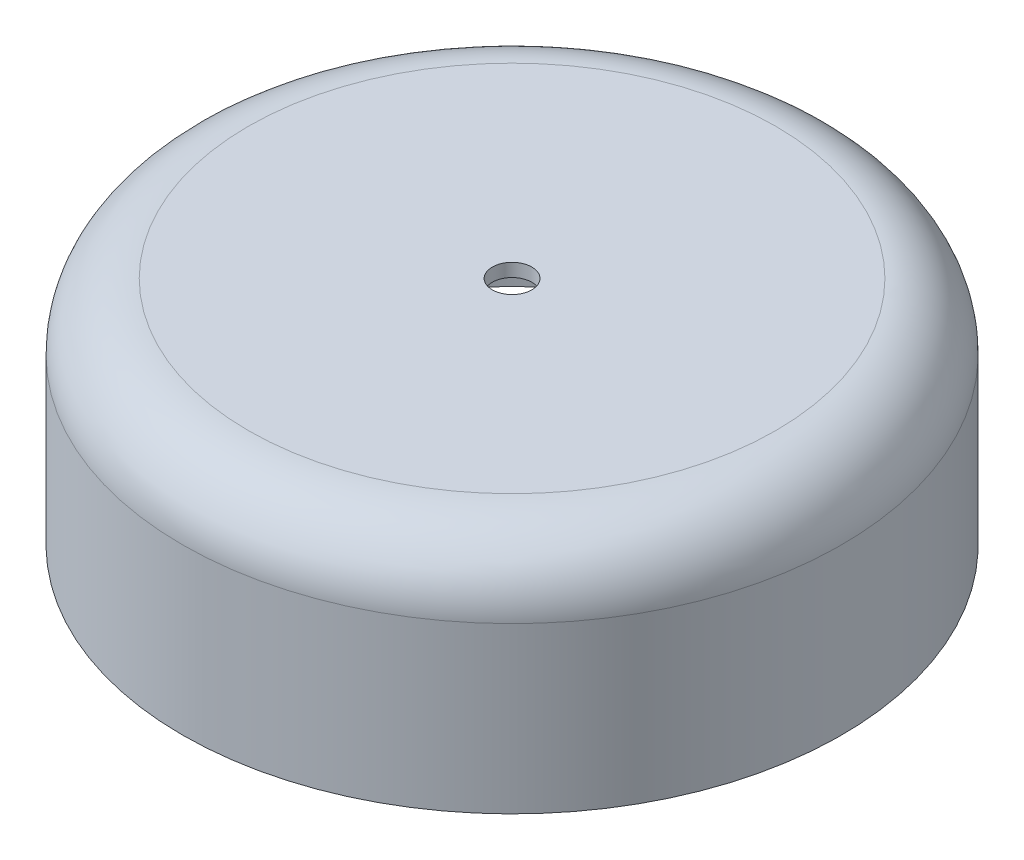
SolidWorks part; units mm, degrees
ref_plane "Front Plane" through (0, 0, 0) normal (0, 0, 1) x (1, 0, 0)
ref_plane "Top Plane" through (0, 0, 0) normal (0, 1, 0) x (1, 0, 0)
ref_plane "Right Plane" through (0, 0, 0) normal (1, 0, 0) x (0, 0, -1)
sketch "Sketch1" plane through (0, 0, 0) normal (0, 1, 0) x (1, 0, 0)
  circle A0 centre (0, 7.5027) radius 50
  dimension "D1" = 100
extrude "Boss-Extrude1" add sketch "Sketch1" along normal blind 35
fillet "Fillet1" radius 10 1 edges at (0, 35, 42.4973)
shell "Shell1" thickness 2
sketch "Sketch2" plane through (0, 33, 0) normal (0, -1, 0) x (-1, 0, 0)
  line L0 (0, 28.9955) -> (0, -28.9955) construction
  line L2 (-6, -6) -> (6, -6)
  line L3 (-6, -6) -> (-6, -10.5)
  line L4 (-6, -10.5) -> (6, -10.5)
  line L5 (6, -6) -> (6, -10.5)
  line L6 (-6, -6) -> (6, -10.5) construction
  line L7 (-6, -10.5) -> (6, -6) construction
  line L8 (-6, 21.5) -> (6, 21.5)
  line L9 (-6, 21.5) -> (-6, 17)
  line L10 (-6, 17) -> (6, 17)
  line L11 (6, 21.5) -> (6, 17)
  line L12 (-6, 21.5) -> (6, 17) construction
  line L13 (-6, 17) -> (6, 21.5) construction
  point P0 (0, 19.25)
  point P4 (0, 0)
  point P7 (0, -8.25)
  dimension "D1" = 12
  dimension "D2" = 4.5
  dimension "D3" = 12
  dimension "D4" = 4.5
  dimension "D5" = 6
  dimension "D6" = 17
extrude "Boss-Extrude2" add sketch "Sketch2" along normal blind 6.5
sketch "Sketch3" plane through (0, 35, 0) normal (0, 1, 0) x (1, 0, 0)
  circle A0 centre (0, 7.5027) radius 3
  dimension "D1" = 6
extrude "Cut-Extrude1" cut sketch "Sketch3" against normal through all
